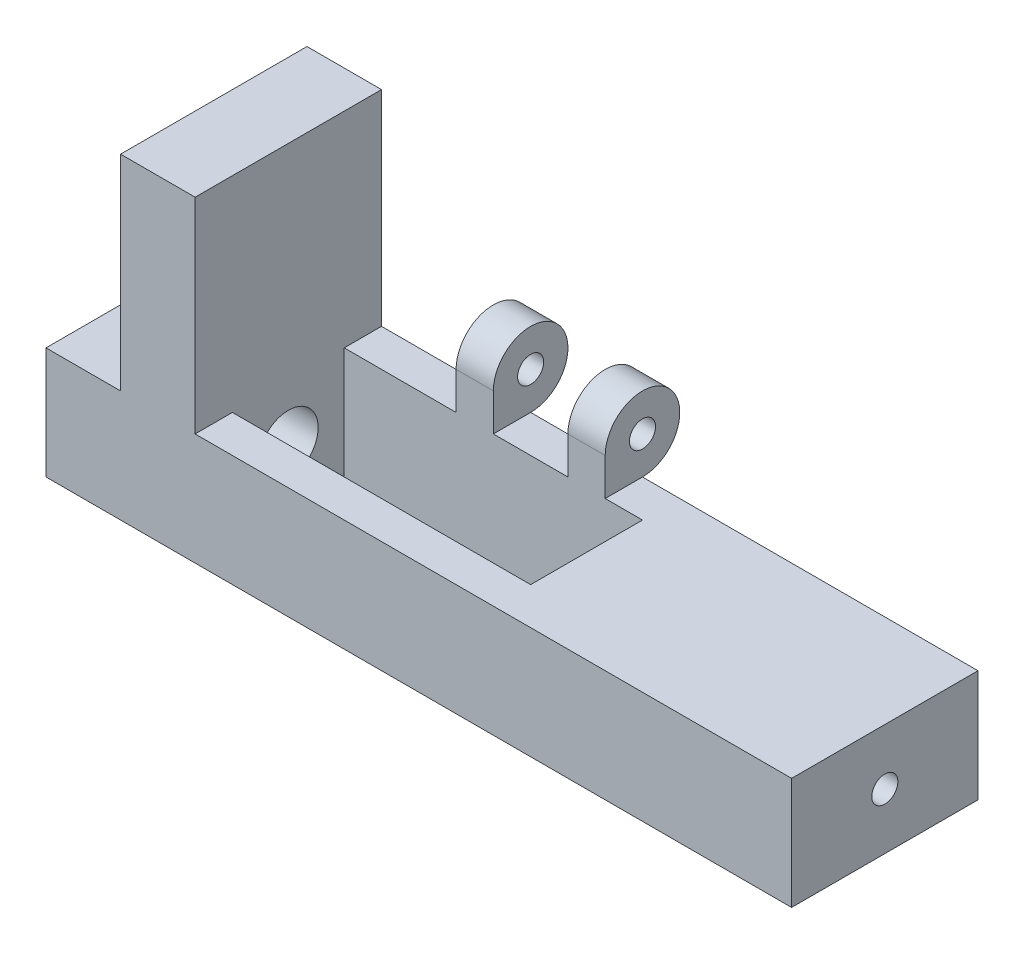
SolidWorks part; units mm, degrees
ref_plane "Front Plane" through (0, 0, 0) normal (0, 0, 1) x (1, 0, 0)
ref_plane "Top Plane" through (0, 0, 0) normal (0, 1, 0) x (1, 0, 0)
ref_plane "Right Plane" through (0, 0, 0) normal (1, 0, 0) x (0, 0, -1)
sketch "Sketch2" plane through (0, 0, 0) normal (0, 1, 0) x (1, 0, 0)
  line L1 (-20, -7.5) -> (20, -7.5)
  line L2 (-20, -7.5) -> (-20, 7.5)
  line L3 (-20, 7.5) -> (20, 7.5)
  line L4 (20, -7.5) -> (20, 7.5)
  line L5 (-20, -7.5) -> (20, 7.5) construction
  line L6 (-20, 7.5) -> (20, -7.5) construction
  line L7 (-40, -12.5) -> (60, -12.5)
  line L8 (-40, -12.5) -> (-40, 12.5)
  line L9 (-40, 12.5) -> (60, 12.5)
  line L10 (60, -12.5) -> (60, 12.5)
  point P0 (0, 0)
  point P10 (-40, 0)
  dimension "D1" = 15
  dimension "D2" = 25
  dimension "D3" = 20
  dimension "D4" = 40
  dimension "D5" = 40
extrude "Boss-Extrude1" add sketch "Sketch2" along normal blind 15
sketch "Sketch3" plane through (60, 0, 0) normal (1, 0, 0) x (0, 0, -1)
  line L0 (0, 0) -> (0, 7.5) construction
  line L1 (-12.5, 0) -> (12.5, 0) construction
  circle A0 centre (0, 7.5) radius 1.75
  dimension "D1" = 3.5
  dimension "D2" = 7.5
extrude "Cut-Extrude1" cut sketch "Sketch3" against normal up to next
sketch "Sketch4" plane through (-40, 0, 0) normal (-1, 0, 0) x (0, 0, 1)
  circle A0 centre (0, 7.5) radius 4
  dimension "D2" = 8
  dimension "D1" = 7.5
extrude "Cut-Extrude2" cut sketch "Sketch4" against normal up to next
sketch "Sketch7" plane through (0, 15, 0) normal (0, 1, 0) x (1, 0, 0)
  line L0 (-40, 12.5) -> (-40, -12.5) construction
  point P0 (-35, 0)
  dimension "D1" = 5
hole_wizard "Ø3.2 (3.2) Diameter Hole1" positions "Sketch7" profile "Sketch6" hole size "Ø3.2" standard "ANSI Metric" end condition through all
sketch "Sketch6" plane through (-35, 15, 0) normal (1, 0, 0) x (0, 0, 1)
  line L0 (0, 0) -> (0, 15)
  line L1 (0, 15) -> (1.6, 15)
  line L2 (1.6, 15) -> (1.6, 0.025)
  line L3 (1.6, 0.025) -> (1.625, 0)
  line L5 (1.625, 0) -> (0, 0)
  line L6 (-1.6, 0.025) -> (-1.625, 0) construction
  line L11 (0, -6.35) -> (0, 107.95) construction
  dimension "Thru Hole Dia." = 3.2
  dimension "Thru Hole Depth" = 15
  dimension "Near C'Sink Dia." = 3.25
  dimension "Near C'Sink Angle" = 90
sketch "Sketch8" plane through (0, 15, 0) normal (0, 1, 0) x (1, 0, 0)
  line L0 (60, 12.5) -> (-40, 12.5) construction
  line L1 (-30, 12.5) -> (-20, 12.5)
  line L2 (-30, 12.5) -> (-30, -12.5)
  line L3 (-30, -12.5) -> (-20, -12.5)
  line L4 (-20, 12.5) -> (-20, -12.5)
  line L5 (-40, -12.5) -> (60, -12.5) construction
  line L6 (-20, 7.5) -> (-20, -7.5) construction
  dimension "D2" = 10
extrude "Boss-Extrude2" add sketch "Sketch8" along normal blind 27.5
sketch "Sketch9" plane through (-20, 0, 0) normal (1, 0, 0) x (0, 0, -1)
  line L4 (7.5, 20) -> (7.5, 15)
  line L5 (7.5, 15) -> (12.5, 15)
  line L6 (12.5, 42.5) -> (12.5, 15) construction
  circle A0 centre (12.5, 20) radius 1.75
  arc A1 (12.5, 15) -> (7.5, 20) centre (12.5, 20) ccw
  point P5 (16.3739, 20)
  point P6 (0, 0)
  point P12 (17.5, 20)
  point P16 (12.7446, 15)
  dimension "D1" = 3.5
extrude "Boss-Extrude3" add sketch "Sketch9" along normal blind 40
sketch "Sketch10" plane through (0, 15, 0) normal (0, 1, 0) x (1, 0, 0)
  line L1 (-20, 17.5) -> (-5, 17.5)
  line L2 (-20, 17.5) -> (-20, 7.5)
  line L3 (-20, 7.5) -> (-5, 7.5)
  line L4 (-5, 17.5) -> (-5, 7.5)
  line L6 (0, 17.5) -> (10, 17.5)
  line L7 (0, 17.5) -> (0, 7.5)
  line L8 (0, 7.5) -> (10, 7.5)
  line L9 (10, 17.5) -> (10, 7.5)
  line L11 (20, 17.5) -> (-20, 17.5) construction
  line L12 (20, 17.5) -> (15, 17.5)
  line L13 (20, 17.5) -> (20, 7.5)
  line L14 (20, 7.5) -> (15, 7.5)
  line L15 (15, 17.5) -> (15, 7.5)
  line L16 (20, 7.5) -> (-20, 7.5) construction
  line L17 (-20, -12.5) -> (-20, 12.5) construction
  line L18 (20, 7.5) -> (20, 17.5) construction
  dimension "D1" = 5
  dimension "D2" = 10
  dimension "D3" = 5
  dimension "D4" = 5
extrude "Cut-Extrude3" cut sketch "Sketch10" along normal up to next
